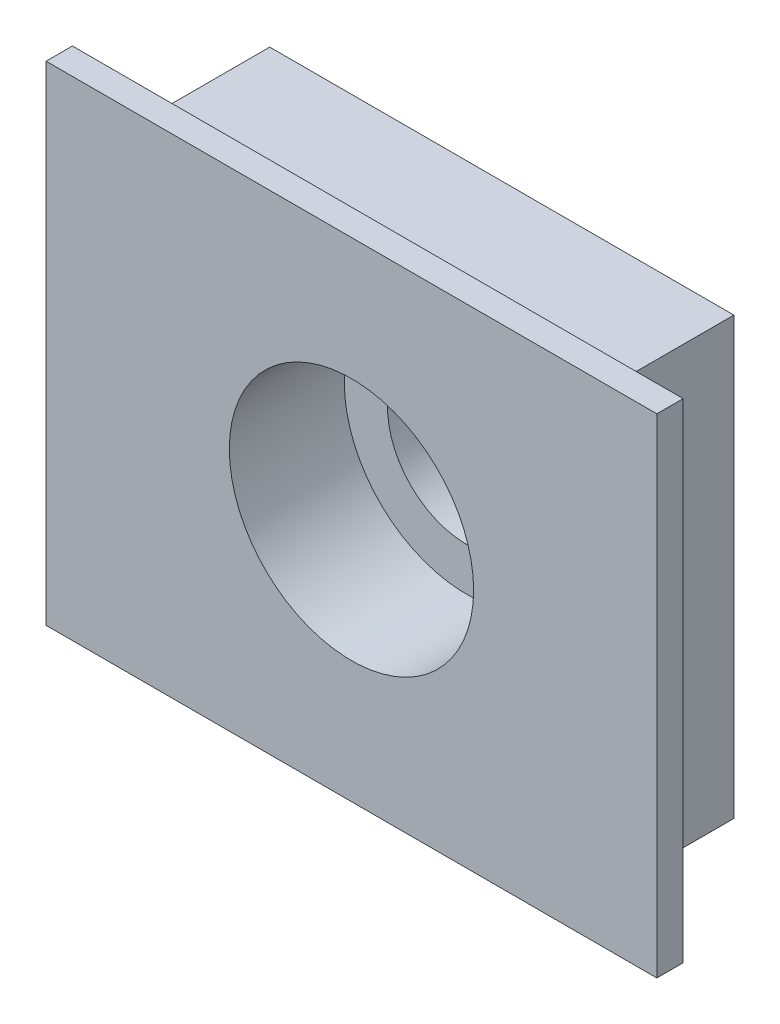
SolidWorks part; units mm, degrees
ref_plane "Front Plane" through (0, 0, 0) normal (0, 0, 1) x (1, 0, 0)
ref_plane "Top Plane" through (0, 0, 0) normal (0, 1, 0) x (1, 0, 0)
ref_plane "Right Plane" through (0, 0, 0) normal (1, 0, 0) x (0, 0, -1)
sketch "Sketch1" plane through (0, 0, 0) normal (0, 0, 1) x (1, 0, 0)
  line L1 (0, 0) -> (325, 0)
  line L2 (0, 0) -> (0, 260)
  line L3 (0, 260) -> (325, 260)
  line L4 (325, 0) -> (325, 260)
  dimension "D1" = 260
  dimension "D2" = 325
extrude "Boss-Extrude1" add sketch "Sketch1" against normal blind 80
sketch "Sketch2" plane through (0, 0, 0) normal (0, 0, 1) x (1, 0, 0)
  line L0 (325, 0) -> (325, 260) construction
  line L1 (325, 260) -> (0, 260) construction
  circle A0 centre (162.5, 130) radius 65
  point P5 (325, 130)
  point P8 (162.5, 260)
  dimension "D1" = 130
extrude "Cut-Extrude1" cut sketch "Sketch2" against normal blind 61.2
sketch "Sketch3" plane through (0, 0, 0) normal (0, 0, 1) x (1, 0, 0)
  circle A0 centre (162.5, 130) radius 42
  dimension "D1" = 84
extrude "Cut-Extrude2" cut sketch "Sketch3" against normal through all
ref_plane "Plane1" through (0, 0, -80) normal (0, 0, -1) x (-1, 0, 0)
sketch "Sketch4" plane through (0, 0, -80) normal (0, 0, -1) x (-1, 0, 0)
  line L1 (-325, 260) -> (0, 260)
  line L2 (-325, 260) -> (-325, 0)
  line L3 (-325, 0) -> (0, 0)
  line L4 (0, 260) -> (0, 0)
  line L5 (-286, 246) -> (-39, 246)
  line L6 (-286, 246) -> (-286, 14)
  line L7 (-286, 14) -> (-39, 14)
  line L8 (-39, 246) -> (-39, 14)
  point P10 (-162.5, 246)
  point P11 (-162.5, 260)
  point P12 (-39, 130)
  point P13 (0, 130)
  dimension "D1" = 14
  dimension "D2" = 39
extrude "Cut-Extrude3" cut sketch "Sketch4" against normal blind 66
